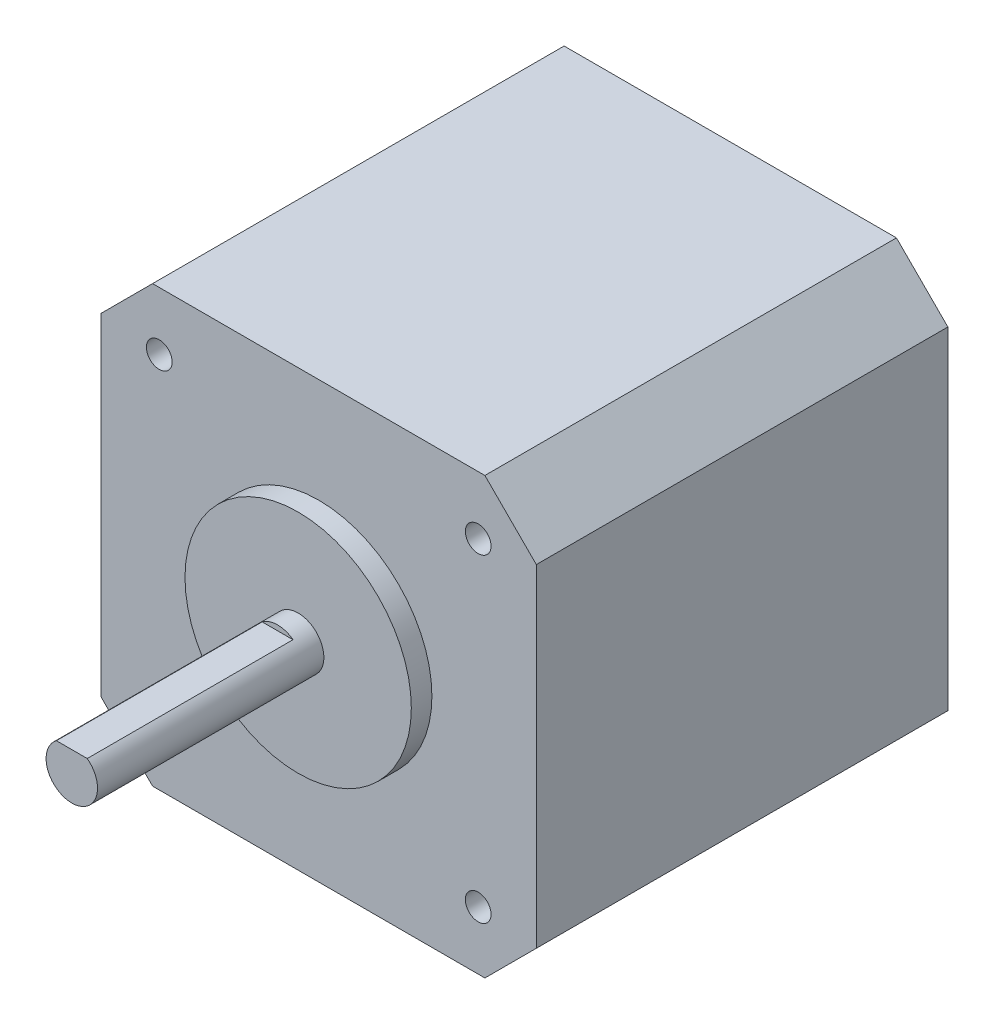
SolidWorks part; units mm, degrees
ref_plane "Vorne" through (0, 0, 0) normal (0, 0, 1) x (1, 0, 0)
ref_plane "Oben" through (0, 0, 0) normal (0, 1, 0) x (1, 0, 0)
ref_plane "Rechts" through (0, 0, 0) normal (1, 0, 0) x (0, 0, -1)
ref_plane "E_Boden" through (0, 1, 0) normal (0, 1, 0) x (1, 0, 0)
sketch "Skizze1" plane through (0, 0, 0) normal (0, 0, 1) x (1, 0, 0)
  line L0 (-52.1949, 0) -> (73.2156, 0) construction
  line L1 (0, 28.6712) -> (0, -41.0344) construction
  line L3 (-20.7678, 14.3726) -> (21.5322, 14.3726)
  line L4 (-20.7678, 14.3726) -> (-20.7678, -27.9274)
  line L5 (-20.7678, -27.9274) -> (21.5322, -27.9274)
  line L6 (21.5322, 14.3726) -> (21.5322, -27.9274)
  dimension "D1" = 42.3
  dimension "D2" = 42.3
extrude "Aufsatz-Linear austragen1" add sketch "Skizze1" along normal blind 40
sketch "Skizze2" plane through (0, 0, 40) normal (0, 0, 1) x (1, 0, 0)
  line L0 (0.3822, 14.3726) -> (0.3822, -27.9274) construction
  line L1 (21.5322, 14.3726) -> (-20.7678, 14.3726) construction
  line L2 (-20.7678, -27.9274) -> (21.5322, -27.9274) construction
  line L3 (-20.7678, -6.7774) -> (21.5322, -6.7774) construction
  line L4 (-20.7678, 14.3726) -> (-20.7678, -27.9274) construction
  line L5 (21.5322, -27.9274) -> (21.5322, 14.3726) construction
  circle A0 centre (0.3822, -6.7774) radius 11
  dimension "D1" = 22
extrude "Aufsatz-Linear austragen2" add sketch "Skizze2" along normal blind 2
sketch "Skizze3" plane through (0, 0, 42) normal (0, 0, 1) x (1, 0, 0)
  line L0 (0.3822, 14.3726) -> (0.3822, -27.9274) construction
  line L1 (21.5322, 14.3726) -> (-20.7678, 14.3726) construction
  line L2 (-20.7678, -27.9274) -> (21.5322, -27.9274) construction
  line L3 (-20.7678, -6.7774) -> (21.5322, -6.7774) construction
  line L4 (-20.7678, 14.3726) -> (-20.7678, -27.9274) construction
  line L5 (21.5322, -27.9274) -> (21.5322, 14.3726) construction
  circle A0 centre (0.3822, -6.7774) radius 2.5
  dimension "D1" = 5
extrude "Aufsatz-Linear austragen3" add sketch "Skizze3" along normal blind 22
sketch "Skizze4" plane through (0, 0, 64) normal (0, 0, 1) x (1, 0, 0)
  line L0 (0.3822, -4.2774) -> (0.3822, -9.2774) construction
  line L1 (-2.1178, -6.7774) -> (2.8822, -6.7774) construction
  line L3 (-2.1178, -4.2774) -> (2.8822, -4.2774)
  line L4 (-2.1178, -4.2774) -> (-2.1178, -4.7774)
  line L5 (-2.1178, -4.7774) -> (2.8822, -4.7774)
  line L6 (2.8822, -4.2774) -> (2.8822, -4.7774)
  circle A0 centre (0.3822, -6.7774) radius 2.5 construction
  circle A1 centre (0.3822, -6.7774) radius 2.5 construction
  dimension "D1" = 0.5
  dimension "D2" = 5
extrude "Schnitt-Linear austragen1" cut sketch "Skizze4" against normal blind 20
hole_wizard "M3 Gewindebohrung2" positions "Skizze9" profile "Skizze10" tap size "M3" standard "DIN"
sketch "Skizze9" plane through (0, 0, 40) normal (0, 0, 1) x (1, 0, 0)
  line L0 (0.3822, 14.3726) -> (0.3822, -27.9274) construction
  line L1 (21.5322, 14.3726) -> (-20.7678, 14.3726) construction
  line L2 (-20.7678, -27.9274) -> (21.5322, -27.9274) construction
  line L4 (-20.7678, -6.7774) -> (21.5322, -6.7774) construction
  line L5 (-20.7678, 14.3726) -> (-20.7678, -27.9274) construction
  line L6 (21.5322, -27.9274) -> (21.5322, 14.3726) construction
  point P0 (-15.1178, 8.7226)
  point P2 (15.8822, 8.7226)
  point P4 (-15.1178, -22.2774)
  point P6 (15.8822, -22.2774)
  point P25 (0, 0)
  point P26 (0, 0)
  point P27 (0, 0)
  point P28 (-14.4861, 10.1176)
  point P33 (16.8203, -18.1391)
  point P34 (0, 0)
  dimension "D1" = 31
  dimension "D2" = 31
sketch "Skizze10" plane through (-15.1178, 8.7226, 40) normal (1, 0, 0) x (0, -1, 0)
  line L0 (0, 0) -> (0, 9.2511)
  line L1 (0, 9.2511) -> (1.25, 8.5)
  line L2 (1.25, 8.5) -> (1.25, 0)
  line L5 (1.25, 0) -> (0, 0)
  line L10 (0, 9.2511) -> (-1.25, 8.5) construction
  line L11 (0, -6.35) -> (0, 107.95) construction
  dimension "Bohrerdurchmesser" = 2.5
  dimension "Bohrungstiefe" = 8.5
  dimension "Spitzenwinkel" = 118
cosmetic thread "Bohrungsgewinde5" parameters "D1"=6, "D2"=3
cosmetic thread "Bohrungsgewinde6" parameters "D1"=6, "D2"=3
cosmetic thread "Bohrungsgewinde7" parameters "D1"=6, "D2"=3
cosmetic thread "Bohrungsgewinde8" parameters "D1"=6, "D2"=3
chamfer "Fase6" distance 5 angle 45 4 edges at (21.5322, 14.3726, 20) (21.5322, -27.9274, 20) (-20.7678, -27.9274, 20) (-20.7678, 14.3726, 20)
